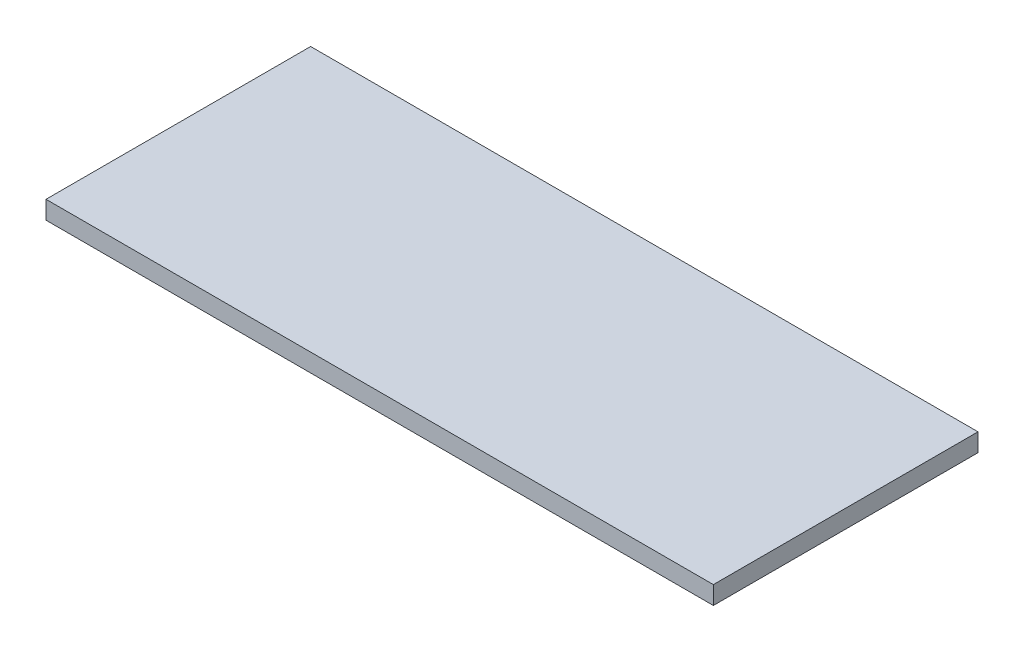
SolidWorks part; units mm, degrees
ref_plane "Front Plane" through (0, 0, 0) normal (0, 0, 1) x (1, 0, 0)
ref_plane "Top Plane" through (0, 0, 0) normal (0, 1, 0) x (1, 0, 0)
ref_plane "Right Plane" through (0, 0, 0) normal (1, 0, 0) x (0, 0, -1)
sketch "Sketch1" plane through (0, 0, 0) normal (0, 1, 0) x (1, 0, 0)
  line L1 (0, 0) -> (368.3, 0)
  line L2 (0, 0) -> (0, 146.05)
  line L3 (0, 146.05) -> (368.3, 146.05)
  line L4 (368.3, 0) -> (368.3, 146.05)
  dimension "D1" = 368.3
  dimension "D2" = 146.05
extrude "Boss-Extrude1" add sketch "Sketch1" along normal blind 10
